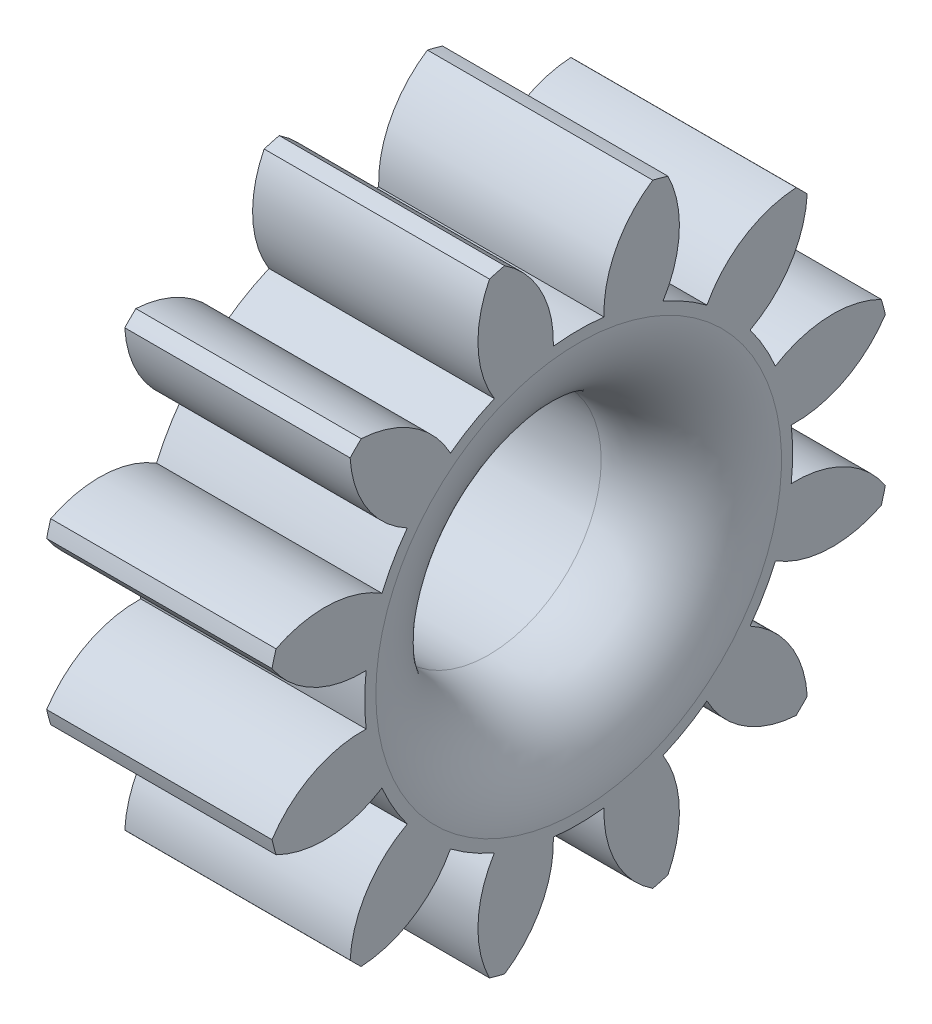
SolidWorks part; units mm, degrees
ref_plane "Plane1" through (0, 0, 0) normal (0, 0, 1) x (1, 0, 0)
ref_plane "Plane2" through (0, 0, 0) normal (0, 1, 0) x (1, 0, 0)
ref_plane "Plane3" through (0, 0, 0) normal (1, 0, 0) x (0, 0, -1)
sketch "HoldingSke" plane through (0, 0, 0) normal (0, 1, 0) x (1, 0, 0)
  line L0 (0, 0) -> (0.9781, -0.2079)
  line L1 (-15, 0) -> (100, 0) construction
  line L2 (0, 0) -> (-2.1039, 2.3779)
  line L3 (0, 0) -> (-11.863, 4.5341)
  line L4 (0, 0) -> (8.4473, 1.7955)
  line L5 (0, 0) -> (-46.8476, -17.4728)
  line L6 (0, 0) -> (-4.1448, -2.7965)
  line L7 (-2.1039, 2.3779) -> (8.6586, 51.2059)
  line L8 (-76.2, 54.61) -> (-75.3, 54.61)
  line L9 (-71.009, 38.7566) -> (-53.1078, 45.2721)
  line L10 (-76.2, 71.12) -> (104.1128, 71.12)
  line L11 (0, 0) -> (-5, 0)
  line L12 (-76.2, 101.6) -> (-76.162, 101.6)
  line L13 (24.9733, 27.94) -> (52.9518, 28.4284)
  line L14 (24.9733, 27.94) -> (24.9743, 27.94)
  line L15 (24.9733, 27.94) -> (100.4006, 29.5858)
  line L16 (-63.627, -1) -> (-12.827, -1)
  circle A0 centre (0, 0) radius 2.5
  circle A1 centre (0, 0) radius 4.749
  circle A2 centre (0, 0) radius 37.5
  circle A3 centre (0, 0) radius 2.5
  dimension "MHD" = 9.498
  dimension "Hub_dia" = 75
  dimension "Bore" = 5
  dimension "MBD" = 5
  dimension "Num_teeth" = 12
  dimension "Pitch" = 1
  dimension "Overall_len" = 50
  dimension "Show_teeth" = 12
  dimension "Thickness" = 5
  dimension "OAL" = 50.0001
  dimension "T_dim" = 0.9
  dimension "Ap" = 20
  dimension "H" = 19.05
  dimension "Pitch_radius" = 180.3128
  dimension "Width" = 5
  dimension "Backlash" = 0.038
  dimension "Addendum_fac" = 1
  dimension "Dedendum_fac" = 1.25
  dimension "Clearance_fac" = 0.25
  dimension "Dedendum_add" = 0.001
  dimension "Module" = 1
sketch "BasProSke" plane through (0, 0, 0) normal (0, 1, 0) x (1, 0, 0)
  line L0 (-10, 0) -> (60, 0) construction
  line L1 (0, 0) -> (0, 7)
  line L2 (0, 0) -> (5, 0)
  line L3 (5, 0) -> (5, 7)
  line L4 (5, 7) -> (0, 7)
  dimension "Thickness" = 5
  dimension "Diameter" = 14
revolve "Base-Revolve" add sketch "BasProSke" angle 360 about L0
sketch "TooCutSke" plane through (0, 0, 0) normal (1, 0, 0) x (0, 0, -1)
  line L1 (0, 0) -> (0, 107) construction
  line L2 (0, 0) -> (-0.8496, 5.9395) construction
  line L3 (0, 0) -> (-3.0836, 11.5081) construction
  line L4 (-0.8496, 5.9395) -> (-1.5418, 5.7541) construction
  arc A0 (0.5622, 4.7156) -> (-0.5622, 4.7156) centre (0, 0) ccw
  arc A1 (1.6729, 6.8233) -> (-1.6729, 6.8233) centre (0, 0) ccw
  circle A2 centre (0, 0) radius 6 construction
  circle A3 centre (0, 0) radius 5.6382 construction
  arc A4 (-0.5622, 4.7156) -> (-1.6729, 6.8233) centre (-2.9608, 4.7982) ccw
  arc A5 (1.6729, 6.8233) -> (0.5622, 4.7156) centre (2.9608, 4.7982) ccw
  dimension "Root_dia" = 9.498
  dimension "Overcut_dia" = 14.0508
  dimension "Pitch_dia" = 12
  dimension "Base_dia" = 11.2763
  dimension "Flank_rad" = 2.4
  dimension "Half_ang" = 15
  dimension "Half_CT" = 0.7167
extrude "ToothCut" cut sketch "TooCutSke" along normal through all
fillet "Breaks" [suppressed] radius 0.02
fillet "RootFillets" [suppressed] radius 0.251
pattern_circular "TeethCuts" count 12 every 30 about axis through (-10, 0, 0) along (1, 0, 0) of "ToothCut", "RootFillets", "Breaks"
sketch "HubNeaOneSke" plane through (0, 0, 0) normal (-1, 0, 0) x (0, 0, 1)
  circle A0 centre (0, 0) radius 4.749
  dimension "Diameter" = 9.498
extrude "HubNearOne" [suppressed] add sketch "HubNeaOneSke" along normal blind 45.0001
sketch "HubNeaBotSke" plane through (0, 0, 0) normal (-1, 0, 0) x (0, 0, 1)
  circle A0 centre (0, 0) radius 4.749
  dimension "Diameter" = 9.498
extrude "HubNearBoth" [suppressed] add sketch "HubNeaBotSke" along normal blind 22.5
ref_plane "FarPln" through (5, 0, 0) normal (1, 0, 0) x (0, 0, -1)
sketch "HubFarSke" plane through (5, 0, 0) normal (1, 0, 0) x (0, 0, -1)
  circle A0 centre (0, 0) radius 4.749
  dimension "Diameter" = 9.498
extrude "HubFar" [suppressed] add sketch "HubFarSke" along normal blind 22.5
sketch "BorSke" plane through (0, 0, 0) normal (1, 0, 0) x (0, 0, -1)
  circle A0 centre (0, 0) radius 2.5
  dimension "Diameter" = 5
extrude "Bore" cut sketch "BorSke" along normal mid plane 100.0001
sketch "KeySke" plane through (0, 0, 0) normal (1, 0, 0) x (0, 0, -1)
  line L0 (-1, 0) -> (-1, 3.4)
  line L1 (-1, 3.4) -> (1, 3.4)
  line L2 (1, 3.4) -> (1, 0)
  line L3 (0, 0) -> (0, 34) construction
  line L4 (-1, 0) -> (1, 0)
  dimension "Offset" = 3.4
  dimension "Width" = 2
extrude "Keyway" [suppressed] cut sketch "KeySke" along normal mid plane 100.0001
pattern_circular "Keyway2" [suppressed] count 2 every 90 about axis through (-10, 0, 0) along (1, 0, 0)
sketch "Croquis1" plane through (5, 0, 0) normal (1, 0, 0) x (0, 0, -1)
  circle A0 centre (0, 0) radius 2.5
fillet "Redondeo1" radius 2 1 edges at (5, 0, 2.5)
equation "' \"Module@HoldingSke\" = 6.35"
equation "' \"Num_teeth@HoldingSke\" = 12"
equation "' \"Ap@HoldingSke\" =  20"
equation "' \"Ap@HoldingSke\" = 20"
equation "' \"Width@HoldingSke\" = 0.5 * 25.4"
equation "' \"Hub_dia@HoldingSke\"= 1 * 25.4"
equation "' \"Hub_dia@HoldingSke\" = 1 * 25.4"
equation "' \"Overall_len@HoldingSke\" = 1.0 * 25.4"
equation "' \"Bore@HoldingSke\" = 0.75 * 25.4"
equation "' \"T_dim@HoldingSke\" = 0.1 * 25.4"
equation "' \"Width@KeySke\" = 0.25 * 25.4"
equation "' \"Show_teeth@HoldingSke\" = 13"
equation "' \"Backlash@HoldingSke\" = 0.009 * 25.4"
equation "' \"Addendum_fac@HoldingSke\" = 1.0"
equation "' \"Dedendum_fac@HoldingSke\" = 1.25"
equation "' \"Dedendum_add@HoldingSke\" = 0.00005 * 25.4"
equation "' \"Clearance_fac@HoldingSke\" = 0.25"
equation "\"Pitch@HoldingSke\" = 1 / \"Module@HoldingSke\""
equation "\"Overcut_dia@TooCutSke\" = (\"Num_teeth@HoldingSke\" + 2 * \"Addendum_fac@HoldingSke\") / \"Pitch@HoldingSke\" + 0.002 * 25.4"
equation "\"Pitch_dia@TooCutSke\" = \"Num_teeth@HoldingSke\" / \"Pitch@HoldingSke\""
equation "\"Base_dia@TooCutSke\" = \"Num_teeth@HoldingSke\" / \"Pitch@HoldingSke\" * cos((\"Ap@HoldingSke\"  * 3.14159265 / 180))"
equation "\"Root_dia@TooCutSke\" = (\"Num_teeth@HoldingSke\" + 2) / \"Pitch@HoldingSke\" - 2 * (\"Addendum_fac@HoldingSke\" + \"Dedendum_fac@HoldingSke\") / \"Pitch@HoldingSke\" - \"Dedendum_add@HoldingSke\" * 2"
equation "\"Half_ang@TooCutSke\" = 180 / \"Num_teeth@HoldingSke\""
equation "\"Half_CT@TooCutSke\" = \"Num_teeth@HoldingSke\" / \"Pitch@HoldingSke\" * sin((3.14159265 / 2 / \"Num_teeth@HoldingSke\")) / 2 - 7 * \"Backlash@HoldingSke\" / 4"
equation "\"Flank_rad@TooCutSke\" = \"Num_teeth@HoldingSke\" / \"Pitch@HoldingSke\" / 5"
equation "\"Radius@RootFillets\" = \"Clearance_fac@HoldingSke\" / \"Pitch@HoldingSke\" + \"Dedendum_add@HoldingSke\""
equation "\"Break_rad@Breaks\" = 0.02 / \"Pitch@HoldingSke\""
equation "\"Thickness@HoldingSke\" = \"Width@HoldingSke\""
equation "\"OAL@HoldingSke\" = \"Thickness@HoldingSke\""
equation "\"MHD@HoldingSke\" = (\"Num_teeth@HoldingSke\" + 2) / \"Pitch@HoldingSke\" - 2 * (\"Addendum_fac@HoldingSke\" + \"Dedendum_fac@HoldingSke\")  / \"Pitch@HoldingSke\" - \"Dedendum_add@HoldingSke\" * 2"
equation "\"MBD@HoldingSke\" = (\"Num_teeth@HoldingSke\" + 2) / \"Pitch@HoldingSke\" - 2 * (\"Addendum_fac@HoldingSke\" + \"Dedendum_fac@HoldingSke\")  / \"Pitch@HoldingSke\" - \"Dedendum_add@HoldingSke\" * 2 - 0.002 * 25.4"
equation "\"MHD@HoldingSke\" = ((sgn( \"MHD@HoldingSke\" - \"Hub_dia@HoldingSke\" )-1)*( \"MHD@HoldingSke\" - \"Hub_dia@HoldingSke\" ))/-2+ \"Hub_dia@HoldingSke\""
equation "\"MBD@HoldingSke\" = ((sgn( \"MBD@HoldingSke\" - \"Bore@HoldingSke\" )-1)*( \"MBD@HoldingSke\" - \"Bore@HoldingSke\" ))/-2+ \"Bore@HoldingSke\""
equation "\"OAL@HoldingSke\" = ((sgn( \"OAL@HoldingSke\" - \"Overall_len@HoldingSke\" )+1)*( \"OAL@HoldingSke\" - \"Overall_len@HoldingSke\" ))/2 + \"Overall_len@HoldingSke\" + 0.000002 * 25.4"
equation "\"Num_teeth@TeethCuts\" = int( \"Show_teeth@HoldingSke\" ) + 1"
equation "\"Num_teeth@TeethCuts\" = ((sgn( \"Num_teeth@TeethCuts\" - \"Num_teeth@HoldingSke\" )-1)*( \"Num_teeth@TeethCuts\" - \"Num_teeth@HoldingSke\" ))/-2+ \"Num_teeth@HoldingSke\""
equation "\"Num_teeth@TeethCuts\" = ((sgn( \"Num_teeth@TeethCuts\" - 2.0)+1)*( \"Num_teeth@TeethCuts\" - 2.0))/2 +2.0"
equation "\"Angle@TeethCuts\" = 360.0 / \"Num_teeth@HoldingSke\""
equation "\"Diameter@BasProSke\" = (\"Num_teeth@HoldingSke\" + 2 * \"Addendum_fac@HoldingSke\") / \"Pitch@HoldingSke\""
equation "\"Thickness@BasProSke\"  = \"Thickness@HoldingSke\""
equation "' \"Fillet_rad@BasProSke\" =  \"Thickness@HoldingSke\" * 0.05"
equation "' \"Fillet_rad@BasProSke\" = \"Thickness@HoldingSke\" * 0.05"
equation "\"MHD@HoldingSke\" = ((sgn( \"MHD@HoldingSke\" - \"Root_dia@TooCutSke\" )-1)*( \"MHD@HoldingSke\" - \"Root_dia@TooCutSke\" ))/-2+ \"Root_dia@TooCutSke\""
equation "\"Diameter@HubNeaOneSke\" = \"MHD@HoldingSke\""
equation "\"Length@HubNearOne\" = \"OAL@HoldingSke\" - \"Thickness@BasProSke\""
equation "\"Diameter@HubNeaBotSke\" = \"MHD@HoldingSke\""
equation "\"Length@HubNearBoth\" = ( \"OAL@HoldingSke\" - \"Thickness@BasProSke\" ) / 2.0"
equation "\"Thickness@FarPln\" = \"Thickness@BasProSke\""
equation "\"Diameter@HubFarSke\" = \"MHD@HoldingSke\""
equation "\"Length@HubFar\" = ( \"OAL@HoldingSke\" - \"Thickness@BasProSke\" ) / 2.0"
equation "\"Diameter@BorSke\" = \"MBD@HoldingSke\""
equation "\"D1@Bore\" = \"OAL@HoldingSke\" * 2.0"
equation "\"D1@Keyway\" = \"OAL@HoldingSke\" * 2.0"
equation "\"Offset@KeySke\" = \"T_dim@HoldingSke\" + \"MBD@HoldingSke\" / 2.0"
